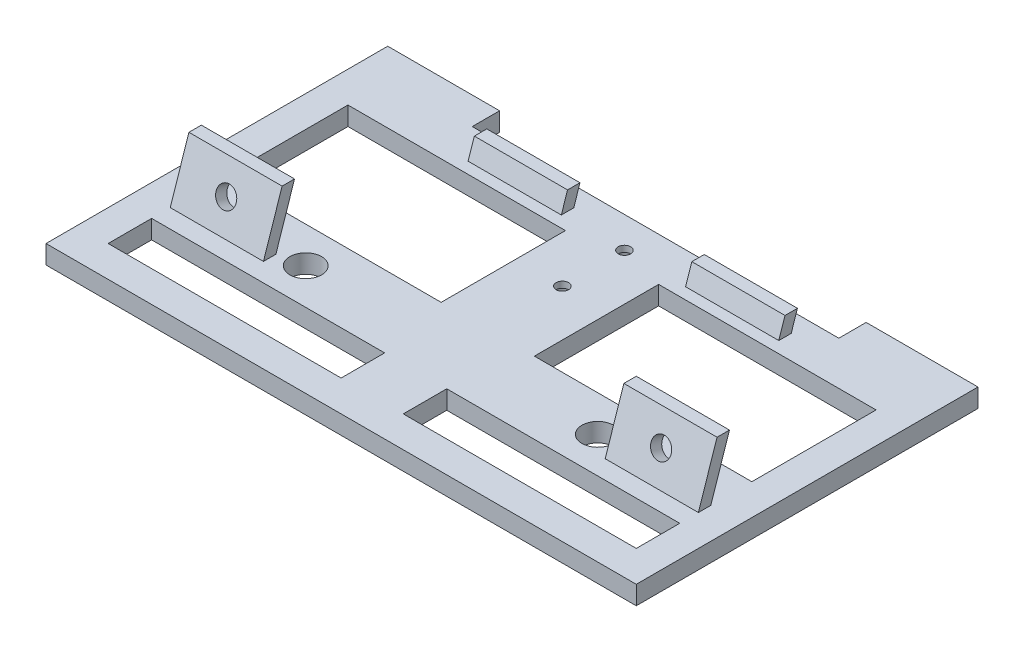
SolidWorks part; units mm, degrees
ref_plane "Alzado" through (0, 0, 0) normal (0, 0, 1) x (1, 0, 0)
ref_plane "Planta" through (0, 0, 0) normal (0, 1, 0) x (1, 0, 0)
ref_plane "Vista lateral" through (0, 0, 0) normal (1, 0, 0) x (0, 0, -1)
sketch "Croquis1" plane through (0, 0, 0) normal (0, 1, 0) x (1, 0, 0)
  line L0 (-47.5, -24.3375) -> (47.5, -24.3375)
  line L1 (47.5, -24.3375) -> (47.5, 30.6625)
  line L2 (47.5, 30.6625) -> (29.5, 30.6625)
  line L3 (29.5, 30.6625) -> (29.5, 26.2625)
  line L4 (29.5, 26.2625) -> (-29.5, 26.2625)
  line L5 (-29.5, 26.2625) -> (-29.5, 30.6625)
  line L6 (-29.5, 30.6625) -> (-47.5, 30.6625)
  line L7 (-47.5, 30.6625) -> (-47.5, -24.3375)
  line L8 (0, 26.2625) -> (0, -24.3375) construction
  line L9 (-17.25, 3.1625) -> (38.85, 3.1625) construction
  line L10 (-42.5, -0.7375) -> (-7.5, -0.7375)
  line L11 (42.5, 19.2625) -> (7.5, 19.2625)
  line L12 (42.5, 19.2625) -> (42.5, -0.7375)
  line L13 (42.5, -0.7375) -> (7.5, -0.7375)
  line L14 (7.5, 19.2625) -> (7.5, -0.7375)
  line L15 (-42.5, 19.2625) -> (-42.5, -0.7375)
  line L16 (-42.5, 19.2625) -> (-7.5, 19.2625)
  line L17 (-7.5, 19.2625) -> (-7.5, -0.7375)
  line L18 (-5, -19.3375) -> (-42.5, -19.3375)
  line L19 (5, -12.3375) -> (42.5, -12.3375)
  line L20 (5, -12.3375) -> (5, -19.3375)
  line L21 (5, -19.3375) -> (42.5, -19.3375)
  line L22 (42.5, -12.3375) -> (42.5, -19.3375)
  line L23 (-42.5, -12.3375) -> (-42.5, -19.3375)
  line L24 (-5, -12.3375) -> (-42.5, -12.3375)
  line L25 (-5, -12.3375) -> (-5, -19.3375)
  circle A0 centre (0, 21.2625) radius 1
  circle A1 centre (0, 11.2625) radius 1
  dimension "D9" = 2
  dimension "D10" = 2
  dimension "D1" = 27.5
  dimension "D2" = 27.5
  dimension "D3" = 29.5
  dimension "D4" = 29.5
  dimension "D5" = 47.5
  dimension "D6" = 47.5
  dimension "D7" = 5
  dimension "D8" = 10
  dimension "D11" = 35
  dimension "D12" = 5
  dimension "D13" = 7
  dimension "D14" = 20
  dimension "D15" = 5
  dimension "D16" = 7
  dimension "D17" = 5
  dimension "D18" = 37.5
extrude "Saliente-Extruir1" add sketch "Croquis1" along normal blind 3
sketch "Sketch2" plane through (29.5, 0, 0) normal (-1, 0, 0) x (0, 0, 1)
  line L0 (-26.2625, 3) -> (-25.2625, 0)
  line L1 (-25.2625, 0) -> (-26.2625, 0)
  line L2 (-26.2625, 0) -> (-26.2625, 3)
  dimension "D1" = 1
extrude "Cut-Extrude1" cut sketch "Sketch2" along normal up to vertex (59 mm away) up to point (-29.5, 0, -26.2625)
sketch "Sketch3" plane through (0, 0, 0) normal (0, -1, 0) x (1, 0, 0)
  circle A0 centre (0, -11.2625) radius 2.75
  circle A1 centre (0, -21.2625) radius 2.75
  dimension "D1" = 5.5
  dimension "D2" = 5.5
extrude "Cut-Extrude2" cut sketch "Sketch3" against normal blind 2
sketch "Croquis2" plane through (0, 3, 0) normal (0, 1, 0) x (1, 0, 0)
  line L0 (0, -24.1369) -> (0, 26.4631) construction
  line L4 (-5, -12.3375) -> (-42.5, -12.3375) construction
  circle A0 centre (-23.5, -6.5375) radius 2.55
  circle A1 centre (23.5, -6.5375) radius 2.55
  dimension "D1" = 5.1
  dimension "D2" = 23.5
  dimension "D3" = 5.8
extrude "Cortar-Extruir1" cut sketch "Croquis2" against normal up to next
sketch "Croquis3" plane through (47.5, 0, 0) normal (1, 0, 0) x (0, 0, -1)
  line L0 (-9.3375, 3) -> (-6.3375, 12)
  line L2 (21.1025, 3) -> (22.1025, 6)
  line L3 (-24.3375, 3) -> (30.6625, 3) construction
  line L4 (22.1025, 6) -> (24.1025, 6)
  line L5 (24.1025, 6) -> (23.1025, 3)
  line L6 (23.1025, 3) -> (21.1025, 3)
  line L7 (25.2625, 0) -> (25.2625, 3) construction
  line L9 (-6.3375, 12) -> (-4.3375, 12)
  line L10 (-4.3375, 12) -> (-7.3375, 3)
  line L11 (-7.3375, 3) -> (-9.3375, 3)
  dimension "D1" = 2.16
  dimension "D2" = 2
  dimension "D3" = 1
  dimension "D4" = 3
  dimension "D5" = 2
  dimension "D6" = 3
  dimension "D7" = 9
  dimension "D8" = 15
extrude "Saliente-Extruir6" add sketch "Croquis3" against normal blind 95 separate body
sketch "Croquis4" plane through (0, 0, -30.6625) normal (0, 0, -1) x (-1, 0, 0)
  line L0 (0, 3) -> (0, 9.922) construction
  line L2 (47.5, 3) -> (-47.5, 3) construction
  line L3 (-10, 6.003) -> (10, 6.003)
  line L4 (-10, 6.003) -> (-10, 3)
  line L5 (-10, 3) -> (10, 3)
  line L6 (10, 6.003) -> (10, 3)
  line L7 (-10, 6.003) -> (10, 3) construction
  line L8 (-10, 3) -> (10, 6.003) construction
  line L9 (-47.5, 6) -> (-47.5, 3)
  line L10 (47.5, 6) -> (25, 6)
  line L11 (47.5, 6) -> (47.5, 3)
  line L12 (47.5, 3) -> (25, 3)
  line L13 (25, 6) -> (25, 3)
  line L14 (-47.5, 3) -> (-25, 3)
  line L15 (-47.5, 6) -> (-25, 6)
  line L16 (-25, 6) -> (-25, 3)
  point P1 (0, 4.5015)
  dimension "D1" = 10
  dimension "D2" = 22.5
extrude "Cortar-Extruir2" cut sketch "Croquis4" against normal blind 95
sketch "Croquis5" plane through (0, 0, 24.3375) normal (0, 0, 1) x (1, 0, 0)
  line L0 (-47.5, 12) -> (47.5, 12) construction
  line L1 (47.5, 3) -> (42.5, 3)
  line L2 (47.5, 3) -> (47.5, 12)
  line L3 (47.5, 12) -> (42.5, 12)
  line L4 (42.5, 3) -> (42.5, 12)
  line L5 (0, 0) -> (0, 12) construction
  line L6 (-47.5, 3) -> (-42.5, 3)
  line L7 (-47.5, 3) -> (-47.5, 12)
  line L8 (-47.5, 12) -> (-42.5, 12)
  line L9 (-42.5, 3) -> (-42.5, 12)
  line L10 (-47.5, 3) -> (47.5, 3) construction
  line L11 (-27.5, 12) -> (27.5, 12)
  line L12 (-27.5, 12) -> (-27.5, 3)
  line L13 (-27.5, 3) -> (27.5, 3)
  line L14 (27.5, 12) -> (27.5, 3)
  line L15 (-27.5, 12) -> (27.5, 3) construction
  line L16 (-27.5, 3) -> (27.5, 12) construction
  point P14 (0, 7.5)
  dimension "D1" = 5
  dimension "D2" = 55
extrude "Cortar-Extruir3" cut sketch "Croquis5" against normal blind 30
sketch "Croquis6" plane through (0, 3.1012, 9.3038) normal (0, 0.3162, 0.9487) x (1, 0, 0)
  line L0 (0, -7.6962) -> (0, 12.3861) construction
  circle A0 centre (-35, 4.6367) radius 1.625
  circle A1 centre (35, 4.6367) radius 1.625
  dimension "D1" = 3.25
extrude "Cortar-Extruir4" cut sketch "Croquis6" against normal up to next (1.8974 mm away)
